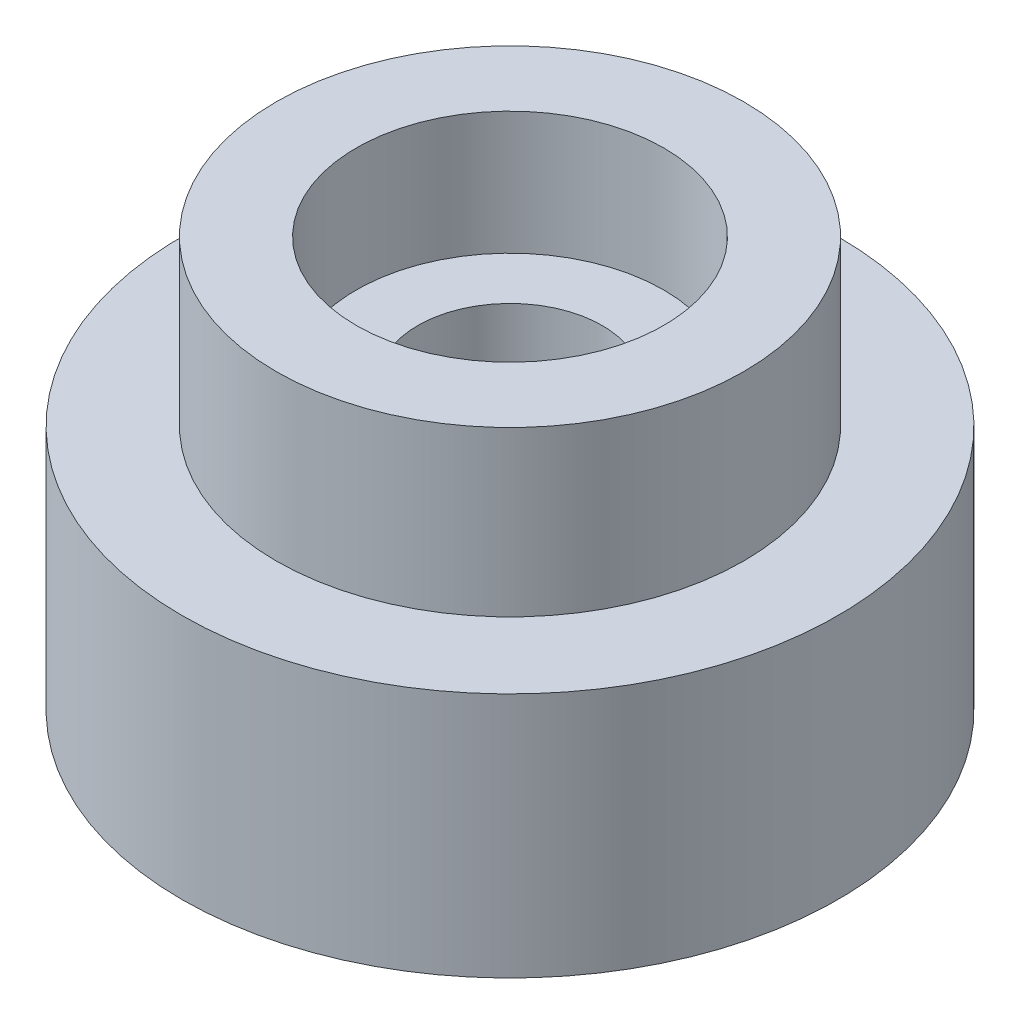
SolidWorks part; units mm, degrees
ref_plane "Front" through (0, 0, 0) normal (0, 0, 1) x (1, 0, 0)
ref_plane "Top" through (0, 0, 0) normal (0, 1, 0) x (1, 0, 0)
ref_plane "Right" through (0, 0, 0) normal (1, 0, 0) x (0, 0, -1)
sketch "Croquis1" plane through (0, 0, 0) normal (0, 1, 0) x (1, 0, 0)
  circle A0 centre (0, 0) radius 4
  dimension "D1" = 8
extrude "Saliente-Extruir1" add sketch "Croquis1" along normal blind 3
sketch "Croquis2" plane through (0, 3, 0) normal (0, 1, 0) x (1, 0, 0)
  circle A0 centre (0, 0) radius 2.85
  dimension "D1" = 5.7
extrude "Saliente-Extruir2" add sketch "Croquis2" along normal blind 2
sketch "Croquis3" plane through (0, 5, 0) normal (0, 1, 0) x (1, 0, 0)
  circle A0 centre (0, 0) radius 1.125
  dimension "D1" = 2.25
extrude "Cortar-Extruir1" cut sketch "Croquis3" against normal through all
sketch "Croquis4" plane through (0, 5, 0) normal (0, 1, 0) x (1, 0, 0)
  circle A0 centre (0, 0) radius 1.875
  dimension "D1" = 3.75
extrude "Cortar-Extruir2" cut sketch "Croquis4" against normal blind 1.5
